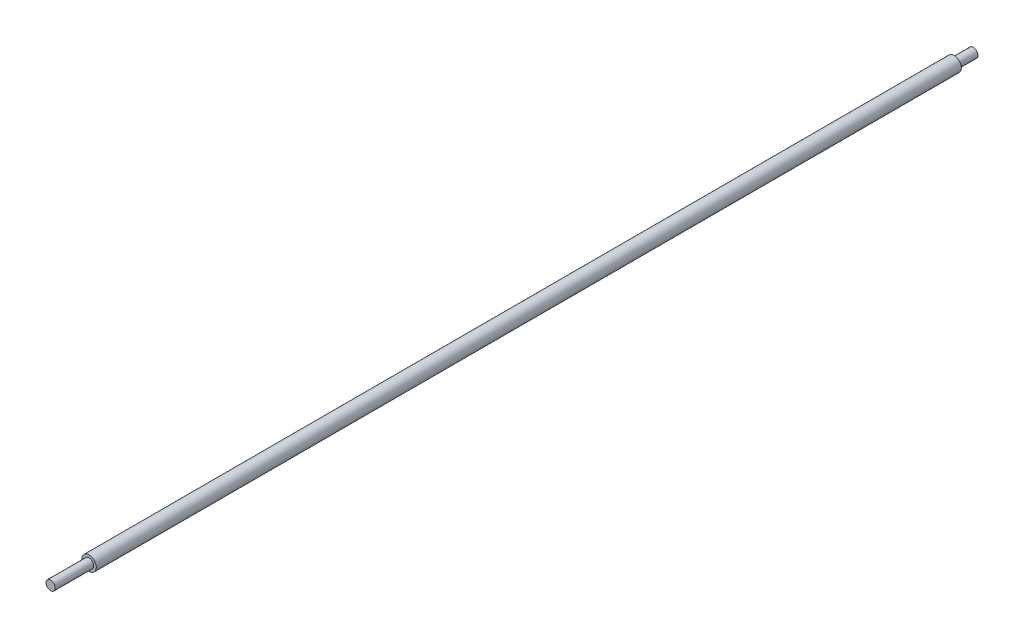
SolidWorks part; units mm, degrees
material "AISI 304"
ref_plane "Front Plane" through (0, 0, 0) normal (0, 0, 1) x (1, 0, 0)
ref_plane "Top Plane" through (0, 0, 0) normal (0, 1, 0) x (1, 0, 0)
ref_plane "Right Plane" through (0, 0, 0) normal (1, 0, 0) x (0, 0, -1)
sketch "Sketch1" plane through (0, 0, 0) normal (0, 0, 1) x (1, 0, 0)
  circle A0 centre (0, 0) radius 4.7625
  dimension "D1" = 9.525
extrude "Boss-Extrude1" add sketch "Sketch1" along normal blind 609.6
sketch "Sketch2" plane through (0, 0, 609.6) normal (0, 0, 1) x (1, 0, 0)
  circle A1 centre (0, 0) radius 4.7625
  circle A2 centre (0, 0) radius 4.7625
  circle A6 centre (0, 0) radius 3.0607
  circle A7 centre (0, 0) radius 3.0607
  dimension "D1" = 0
  dimension "D2" = 1.7018
extrude "Cut-Extrude1" cut sketch "Sketch2" against normal blind 25.4
sketch "Sketch3" plane through (0, 0, 0) normal (0, 0, -1) x (-1, 0, 0)
  circle A1 centre (0, 0) radius 4.7625
  circle A2 centre (0, 0) radius 4.7625
  circle A5 centre (0, 0) radius 3.0607
  circle A6 centre (0, 0) radius 3.0607
  dimension "D1" = 0
  dimension "D2" = 1.7018
extrude "Cut-Extrude3" cut sketch "Sketch3" against normal blind 12.7
thread "Thread1" pitch 1.5875 start angle 0, offset 0, length 571.5, pitch 1.5875, diameter 9.525
ref_plane "Plane2" through (4.7625, 0, 12.7) normal (0, -1, 0) x (1, 0, 0)
sketch "Thread Profile2" plane through (4.7625, 0, 12.7) normal (0, -1, 0) x (1, 0, 0)
  line L0 (0, 0) -> (0, 1.5875) construction
  line L11 (0, 0) -> (0, 1.3891)
  line L12 (0, 1.3891) -> (-0.8593, 0.893)
  line L13 (-0.8593, 0.893) -> (-0.8593, 0.4961)
  line L15 (-0.8593, 0.4961) -> (0, 0)
  line L17 (-0.8593, 0.6945) -> (0, 0.6945) construction
  point P2 (0, 0)
  dimension "Pitch" = 1.5875
  dimension "Profile_Angle" = 60
  dimension "Profile_Land" = 0.3969
  dimension "Profile_Height" = 0.8593
